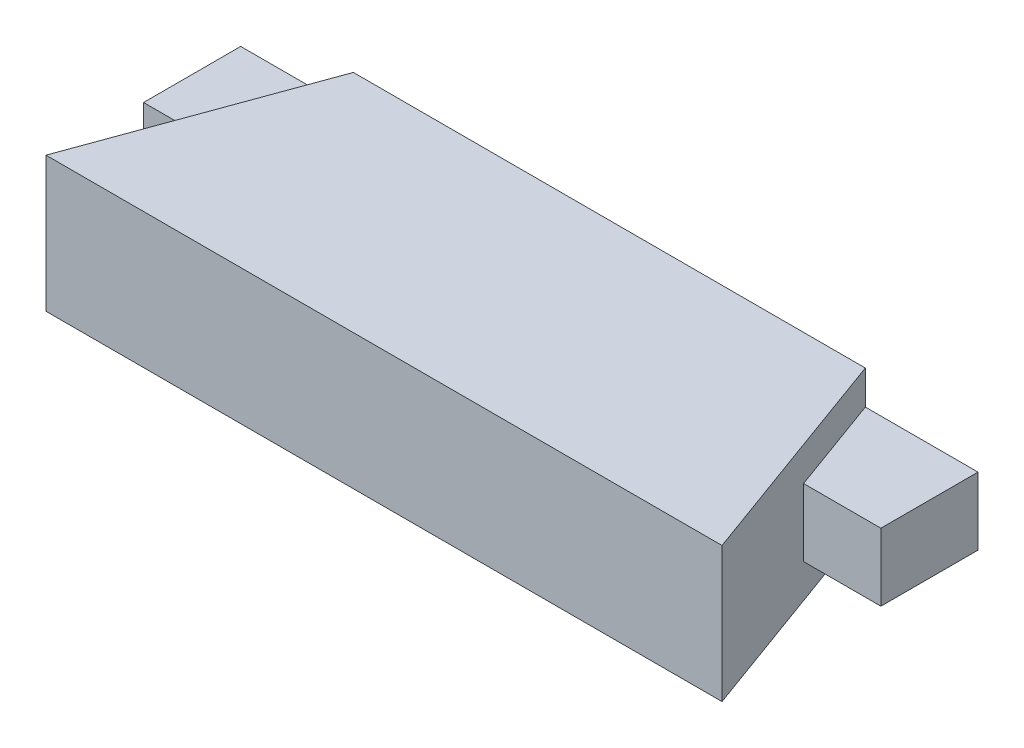
SolidWorks part; units mm, degrees
ref_plane "Alzado" through (0, 0, 0) normal (0, 0, 1) x (1, 0, 0)
ref_plane "Planta" through (0, 0, 0) normal (0, 1, 0) x (1, 0, 0)
ref_plane "Vista lateral" through (0, 0, 0) normal (1, 0, 0) x (0, 0, -1)
sketch "Croquis3" plane through (0, 0, 0) normal (0, 1, 0) x (1, 0, 0)
  line L0 (-75, 0) -> (75, 0)
  line L2 (-75, 0) -> (-56.8015, 50)
  line L4 (75, 0) -> (56.8015, 50)
  line L6 (-56.8015, 50) -> (56.8015, 50)
  point P2 (0, 0)
  dimension "D1" = 150
  dimension "D2" = 70
  dimension "D3" = 70
  dimension "D4" = 50
  dimension "D5" = 50
extrude "Saliente-Extruir4" add sketch "Croquis3" along normal blind 30
sketch "Croquis6" plane through (0, 0, -50) normal (0, 0, -1) x (-1, 0, 0)
  line L5 (-56.8015, 30) -> (56.8015, 30) construction
  line L7 (-81.8, 22.5) -> (81.8, 22.5)
  line L8 (-81.8, 22.5) -> (-81.8, 7.5)
  line L9 (-81.8, 7.5) -> (81.8, 7.5)
  line L10 (81.8, 22.5) -> (81.8, 7.5)
  line L11 (-56.8015, 30) -> (-56.8015, 0) construction
  point P6 (0, 30)
  point P7 (0, 22.5)
  point P8 (-81.8, 15)
  point P12 (-56.8015, 15)
  dimension "D1" = 163.6
  dimension "D2" = 15
extrude "Saliente-Extruir6" add sketch "Croquis6" against normal blind 21.55
